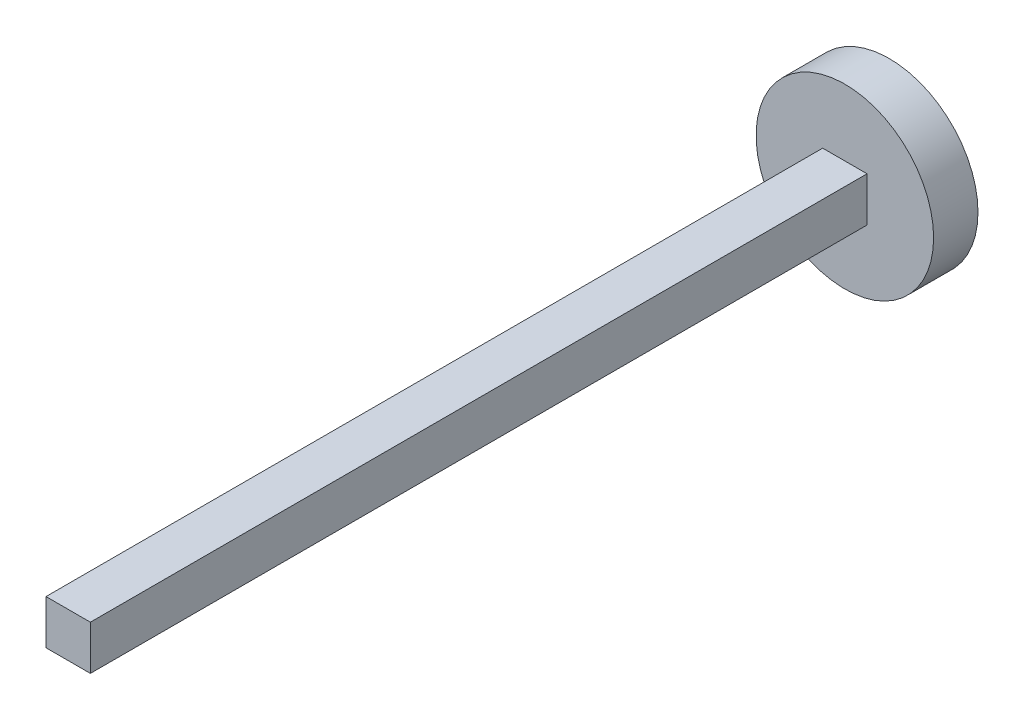
SolidWorks part; units mm, degrees
ref_plane "Front Plane" through (0, 0, 0) normal (0, 0, 1) x (1, 0, 0)
ref_plane "Top Plane" through (0, 0, 0) normal (0, 1, 0) x (1, 0, 0)
ref_plane "Right Plane" through (0, 0, 0) normal (1, 0, 0) x (0, 0, -1)
sketch "Sketch1" plane through (0, 0, 0) normal (0, 0, 1) x (1, 0, 0)
  circle A0 centre (0, 0) radius 40
  dimension "D1" = 80
extrude "Boss-Extrude1" add sketch "Sketch1" along normal blind 20
sketch "Sketch2" plane through (0, 0, 20) normal (0, 0, 1) x (1, 0, 0)
  line L5 (-10, -10) -> (10, -10)
  line L6 (-10, -10) -> (-10, 10)
  line L7 (-10, 10) -> (10, 10)
  line L8 (10, -10) -> (10, 10)
  line L9 (-10, -10) -> (10, 10) construction
  line L10 (-10, 10) -> (10, -10) construction
  point P0 (0, 0)
  point P1 (0, 0)
  dimension "D1" = 20
  dimension "D2" = 20
extrude "Boss-Extrude2" add sketch "Sketch2" along normal blind 350
